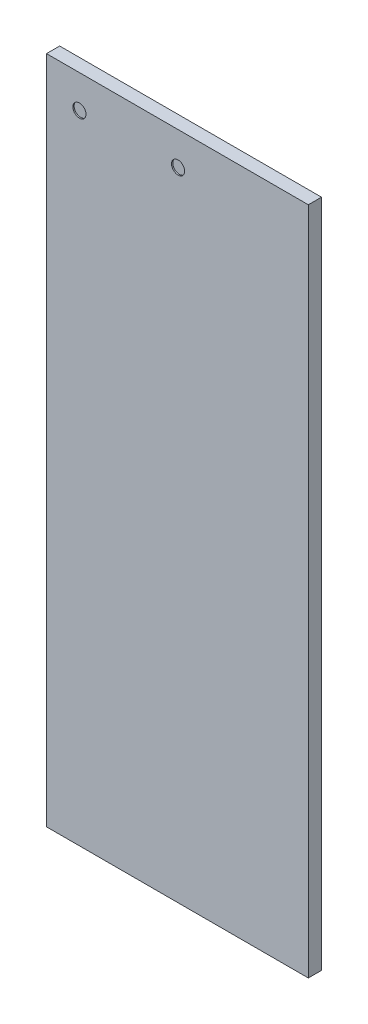
SolidWorks part; units mm, degrees
ref_plane "Front Plane" through (0, 0, 0) normal (0, 0, 1) x (1, 0, 0)
ref_plane "Top Plane" through (0, 0, 0) normal (0, 1, 0) x (1, 0, 0)
ref_plane "Right Plane" through (0, 0, 0) normal (1, 0, 0) x (0, 0, -1)
sketch "Sketch1" plane through (0, 0, 0) normal (0, 0, 1) x (1, 0, 0)
  line L1 (199, -509) -> (-199, -509)
  line L2 (199, -509) -> (199, 509)
  line L3 (199, 509) -> (-199, 509)
  line L4 (-199, -509) -> (-199, 509)
  line L5 (199, -509) -> (-199, 509) construction
  line L6 (199, 509) -> (-199, -509) construction
  point P0 (0, 0)
  dimension "D1" = 1018
  dimension "D2" = 398
extrude "Boss-Extrude1" add sketch "Sketch1" along normal blind 20 contours L4 L3 L2 L1
sketch "Sketch2" plane through (0, 0, 20) normal (0, 0, 1) x (1, 0, 0)
  line L0 (-199, 459) -> (199, 459) construction
  line L1 (-199, -509) -> (-199, 509) construction
  line L2 (199, -509) -> (199, 509) construction
  line L3 (199, 509) -> (-199, 509) construction
  line L4 (-149, 509) -> (-149, -509) construction
  line L5 (199, -509) -> (-199, -509) construction
  line L6 (-149, 459) -> (1, 459) construction
  circle A0 centre (-149, 459) radius 10
  circle A1 centre (1, 459) radius 10
  dimension "D3" = 20
  dimension "D1" = 50
  dimension "D2" = 50
  dimension "D4" = 150
extrude "Cut-Extrude1" cut sketch "Sketch2" against normal blind 2
sketch "Sketch4" plane through (0, 0, 20) normal (0, 0, 1) x (1, 0, 0)
  line L0 (-306.4993, 633.6961) -> (-306.4993, -708.231) construction
